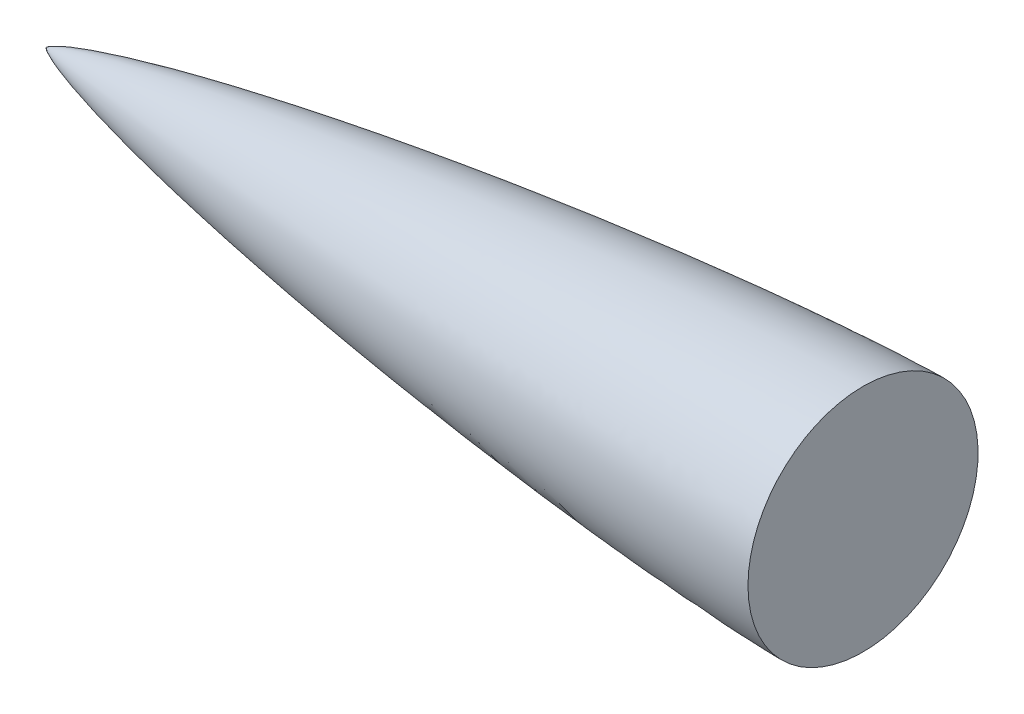
SolidWorks part; units mm, degrees
ref_plane "Front Plane" through (0, 0, 0) normal (0, 0, 1) x (1, 0, 0)
ref_plane "Top Plane" through (0, 0, 0) normal (0, 1, 0) x (1, 0, 0)
ref_plane "Right Plane" through (0, 0, 0) normal (1, 0, 0) x (0, 0, -1)
sketch "Sketch1" plane through (0, 0, 0) normal (0, 0, 1) x (1, 0, 0)
  line L0 (0, 0) -> (600, 0)
  line L1 (600, 0) -> (600, 84.5)
  spline S0 degree 4 poles (0, 0) (0.0015, 0.0065) (0.0054, 0.0192) (0.0164, 0.0435) (0.0438, 0.0892) (0.0873, 0.1482) (0.1481, 0.2188) (0.2661, 0.3404) (0.4064, 0.4654) (0.5665, 0.5954) (0.8141, 0.781) (1.1528, 1.0158) (1.7503, 1.3922) (2.826, 1.9961) (4.712, 2.9312) (8.1378, 4.4179) (14.326, 6.7465) (24.5738, 10.0731) (38.4448, 13.9892) (55.1523, 18.2043) (78.0371, 23.4709) (105.6605, 29.2304) (138.128, 35.3798) (175.4505, 41.8061) (212.8566, 47.7236) (250.3299, 53.1982) (287.8596, 58.2713) (325.4382, 62.9669) (363.0607, 67.297) (400.7234, 71.2625) (438.4238, 74.8535) (476.16, 78.0465) (509.2097, 80.4543) (537.5598, 82.1938) (560.1359, 83.3236) (575.0947, 83.9279) (587.1608, 84.2971) (594.497, 84.4461) (598.1656, 84.4938) (600, 84.5) knots 0 0 0 0 0 0.000044 0.000088 0.000175 0.00035 0.000525 0.0007 0.001289 0.001585 0.001882 0.002736 0.004 0.00623 0.009995 0.01658 0.028562 0.049717 0.080863 0.111393 0.141923 0.204215 0.266508 0.3288 0.391092 0.453384 0.515676 0.577968 0.640261 0.702553 0.764845 0.827137 0.889429 0.920576 0.951722 0.975861 0.98793 1 1 1 1 1 construction
  spline S1 degree 4 poles (0, 0) (0.0015, 0.0065) (0.0054, 0.0192) (0.0164, 0.0435) (0.0438, 0.0892) (0.0873, 0.1482) (0.1481, 0.2188) (0.2661, 0.3404) (0.4064, 0.4654) (0.5665, 0.5954) (0.8141, 0.781) (1.1528, 1.0158) (1.7503, 1.3922) (2.826, 1.9961) (4.712, 2.9312) (8.1378, 4.4179) (14.326, 6.7465) (24.5738, 10.0731) (38.4448, 13.9892) (55.1523, 18.2043) (78.0371, 23.4709) (105.6605, 29.2304) (138.128, 35.3798) (175.4505, 41.8061) (212.8566, 47.7236) (250.3299, 53.1982) (287.8596, 58.2713) (325.4382, 62.9669) (363.0607, 67.297) (400.7234, 71.2625) (438.4238, 74.8535) (476.16, 78.0465) (509.2097, 80.4543) (537.5598, 82.1938) (560.1359, 83.3236) (575.0947, 83.9279) (587.1608, 84.2971) (594.497, 84.4461) (598.1656, 84.4938) (600, 84.5) knots 0 0 0 0 0 0.000044 0.000088 0.000175 0.00035 0.000525 0.0007 0.001289 0.001585 0.001882 0.002736 0.004 0.00623 0.009995 0.01658 0.028562 0.049717 0.080863 0.111393 0.141923 0.204215 0.266508 0.3288 0.391092 0.453384 0.515676 0.577968 0.640261 0.702553 0.764845 0.827137 0.889429 0.920576 0.951722 0.975861 0.98793 1 1 1 1 1
revolve "Revolve1" add sketch "Sketch1" angle 360 about L0
